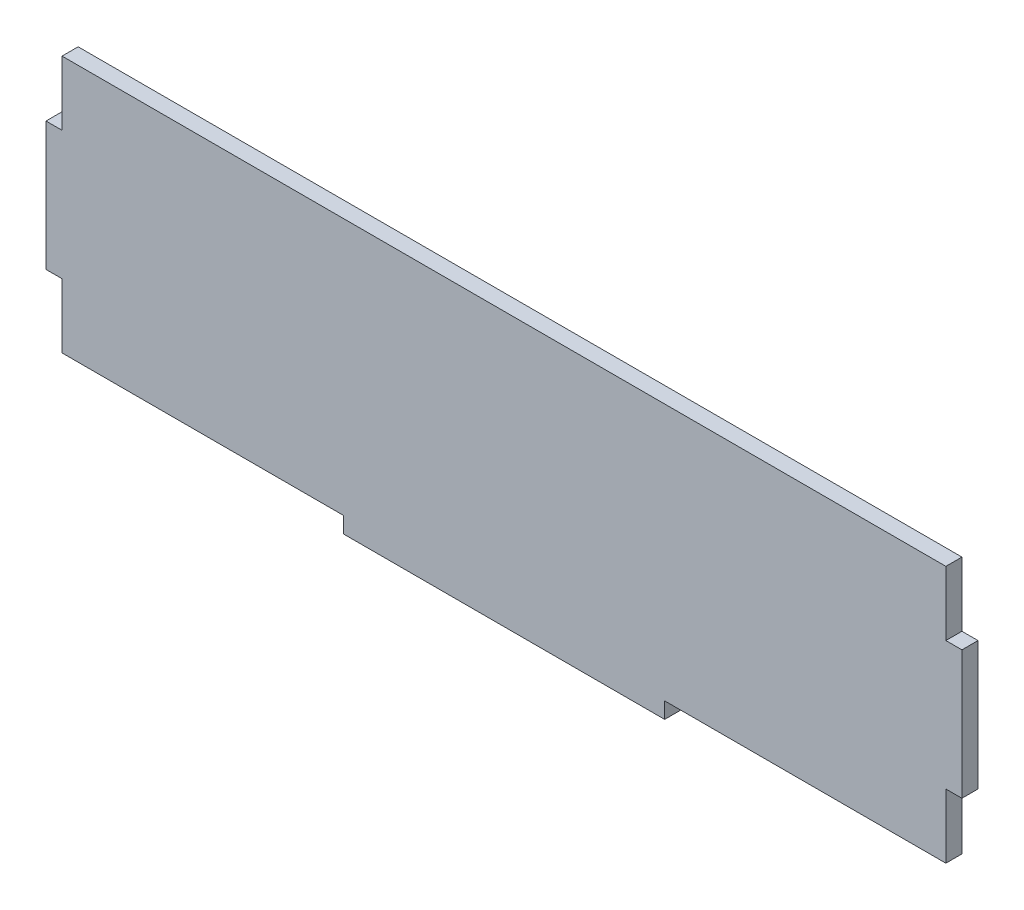
SolidWorks part; units mm, degrees
ref_plane "Ebene vorne" through (0, 0, 0) normal (0, 0, 1) x (1, 0, 0)
ref_plane "Ebene oben" through (0, 0, 0) normal (0, 1, 0) x (1, 0, 0)
ref_plane "Ebene rechts" through (0, 0, 0) normal (1, 0, 0) x (0, 0, -1)
sketch "Skizze1" plane through (0, 0, 0) normal (0, 0, 1) x (1, 0, 0)
  line L1 (0, 0) -> (275, 0)
  line L2 (0, 0) -> (0, 80)
  line L3 (0, 80) -> (275, 80)
  line L4 (275, 0) -> (275, 80)
  dimension "D1" = 275
  dimension "D2" = 80
extrude "Aufsatz-Linear austragen1" add sketch "Skizze1" along normal blind 5
sketch "Skizze2" plane through (0, 0, 5) normal (0, 0, 1) x (1, 0, 0)
  line L0 (137.5, 80) -> (137.5, 0) construction
  line L1 (275, 80) -> (0, 80) construction
  line L2 (0, 0) -> (275, 0) construction
  line L3 (187.5, 0) -> (87.5, 0)
  line L4 (87.5, 0) -> (87.5, -5)
  line L5 (87.5, -5) -> (187.5, -5)
  line L6 (187.5, 0) -> (187.5, -5)
  point P10 (137.5, -5)
  dimension "D1" = 100
  dimension "D2" = 5
extrude "Aufsatz-Linear austragen2" add sketch "Skizze2" against normal through all
sketch "Skizze3" plane through (0, 0, 5) normal (0, 0, 1) x (1, 0, 0)
  line L0 (275, 40) -> (0, 40) construction
  line L1 (0, 80) -> (0, 0) construction
  line L2 (275, 0) -> (275, 80) construction
  line L3 (0, 20) -> (0, 60)
  line L4 (0, 60) -> (-5, 60)
  line L5 (-5, 60) -> (-5, 20)
  line L6 (0, 20) -> (-5, 20)
  line L7 (137.5, -5) -> (137.5, 80) construction
  line L8 (87.5, -5) -> (187.5, -5) construction
  line L9 (275, 80) -> (0, 80) construction
  line L10 (275, 20) -> (280, 20)
  line L11 (280, 60) -> (280, 20)
  line L12 (275, 60) -> (280, 60)
  line L13 (275, 20) -> (275, 60)
  point P10 (-5, 40)
  point P21 (280, 40)
  dimension "D1" = 5
  dimension "D2" = 40
extrude "Aufsatz-Linear austragen3" add sketch "Skizze3" against normal through all
